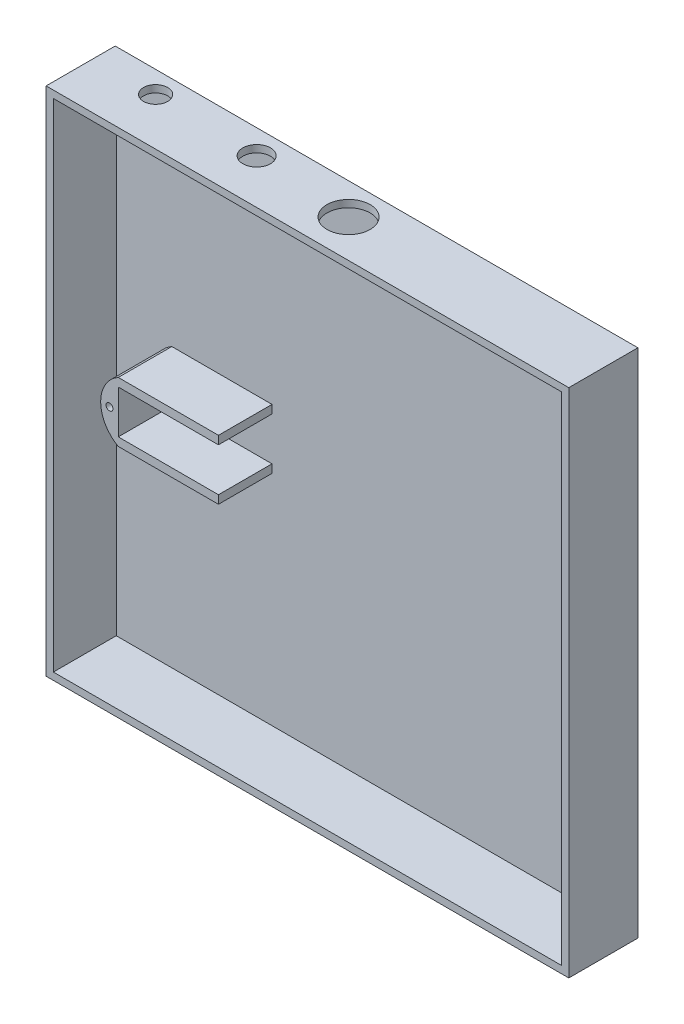
SolidWorks part; units mm, degrees
ref_plane "Alzado" through (0, 0, 0) normal (0, 0, 1) x (1, 0, 0)
ref_plane "Planta" through (0, 0, 0) normal (0, 1, 0) x (1, 0, 0)
ref_plane "Vista lateral" through (0, 0, 0) normal (1, 0, 0) x (0, 0, -1)
sketch "Croquis1" plane through (0, 0, 0) normal (0, 0, 1) x (1, 0, 0)
  line L1 (-181.1322, 61.0984) -> (-29.8322, 61.0984)
  line L2 (-181.1322, 61.0984) -> (-181.1322, -86.9016)
  line L3 (-181.1322, -86.9016) -> (-29.8322, -86.9016)
  line L4 (-29.8322, 61.0984) -> (-29.8322, -86.9016)
  dimension "D1" = 151.3
  dimension "D2" = 148
extrude "Saliente-Extruir1" add sketch "Croquis1" along normal blind 1.8
sketch "Croquis2" plane through (0, 0, 1.8) normal (0, 0, 1) x (1, 0, 0)
  line L9 (-181.1322, 61.0984) -> (-29.8322, 61.0984)
  line L10 (-181.1322, 61.0984) -> (-181.1322, -86.9016)
  line L11 (-181.1322, -86.9016) -> (-29.8322, -86.9016)
  line L12 (-29.8322, 61.0984) -> (-29.8322, -86.9016)
  line L13 (-179.0322, 58.9984) -> (-31.9322, 58.9984)
  line L14 (-179.0322, 58.9984) -> (-179.0322, -84.8016)
  line L15 (-179.0322, -84.8016) -> (-31.9322, -84.8016)
  line L16 (-31.9322, 58.9984) -> (-31.9322, -84.8016)
  dimension "D1" = 2.1
  dimension "D2" = 2.1
  dimension "D3" = 2.1
  dimension "D4" = 2.1
extrude "Saliente-Extruir2" add sketch "Croquis2" along normal blind 18.2
sketch "Croquis4" plane through (0, 61.0984, 0) normal (0, 1, 0) x (1, 0, 0)
  line L0 (-29.8322, 0) -> (-181.1322, 0) construction
  line L1 (-181.1322, -20) -> (-181.1322, 0) construction
  line L2 (-29.8322, -20) -> (-181.1322, -20) construction
  circle A0 centre (-104.4822, -9.1) radius 6.25
  circle A1 centre (-163.1322, -6.3) radius 3.5
  circle A2 centre (-133.1322, -7.05) radius 4
  dimension "D1" = 76.65
  dimension "D3" = 6.3
  dimension "D4" = 7
  dimension "D5" = 7.05
  dimension "D2" = 10.9
  dimension "D6" = 18
  dimension "D7" = 30
extrude "Cortar-Extruir1" cut sketch "Croquis4" against normal up to vertex (2.1 mm away)
sketch "Croquis5" plane through (0, 0, 1.8) normal (0, 0, 1) x (1, 0, 0)
  line L0 (-179.0322, -12.9016) -> (-145.4414, -12.9016) construction
  line L1 (-179.0322, 58.9984) -> (-179.0322, -84.8016) construction
  line L2 (-145.4414, -12.9016) -> (-167.4414, -12.9016) construction
  line L3 (-167.4414, -12.9016) -> (-167.4414, -6.1516) construction
  line L4 (-133.9451, -4.2516) -> (-133.9451, -6.6516)
  line L5 (-162.9451, -6.6516) -> (-133.9451, -6.6516)
  line L7 (-162.9451, -19.1516) -> (-133.9451, -19.1516)
  line L9 (-162.9451, -4.2516) -> (-133.9451, -4.2516)
  line L11 (-162.9451, -21.5516) -> (-133.9451, -21.5516)
  line L13 (-133.9451, -19.1516) -> (-133.9451, -21.5516)
  line L14 (-162.9451, -6.6516) -> (-162.9451, -19.1516)
  line L15 (-162.9451, -21.5516) -> (-162.9451, -4.2516) construction
  circle A1 centre (-165.4951, -12.9016) radius 1
  arc A2 (-162.9451, -4.2516) -> (-162.9451, -21.5516) centre (-158.1596, -12.9016) ccw
  dimension "D1" = 22
  dimension "D7" = 2.55
  dimension "D2" = 6.75
  dimension "D3" = 12.5
  dimension "D4" = 33.5
  dimension "D5" = 2.4
  dimension "D6" = 2.4
  dimension "D11" = 6.25
extrude "Saliente-Extruir3" add sketch "Croquis5" along normal blind 15.5
